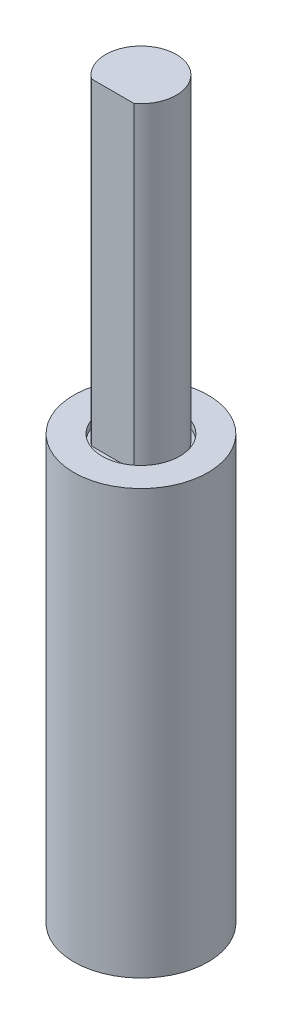
SolidWorks part; units mm, degrees
ref_plane "前视基准面" through (0, 0, 0) normal (0, 0, 1) x (1, 0, 0)
ref_plane "上视基准面" through (0, 0, 0) normal (0, 1, 0) x (1, 0, 0)
ref_plane "右视基准面" through (0, 0, 0) normal (1, 0, 0) x (0, 0, -1)
other "Configuration Table"
sketch "草图1" plane through (0, 0, 0) normal (0, 1, 0) x (1, 0, 0)
  circle A0 centre (0, 0) radius 4.75
  dimension "D1" = 9.5
extrude "凸台-拉伸1" add sketch "草图1" along normal blind 30
sketch "草图2" plane through (0, 30, 0) normal (0, 1, 0) x (1, 0, 0)
  circle A0 centre (0, 0) radius 2.75
  dimension "D1" = 5.5
extrude "切除-拉伸1" cut sketch "草图2" against normal blind 0.5
sketch "草图3" plane through (0, 29.5, 0) normal (0, 1, 0) x (1, 0, 0)
  circle A0 centre (0, 0) radius 2.5
  dimension "D1" = 5
extrude "凸台-拉伸2" add sketch "草图3" along normal blind 22.5
sketch "草图4" plane through (0, 0, 0) normal (0, -1, 0) x (1, 0, 0)
  circle A0 centre (0, 0) radius 2.5
  dimension "D1" = 5
extrude "凸台-拉伸3" add sketch "草图4" along normal blind 0.5
sketch "草图5" plane through (0, 52, 0) normal (0, 1, 0) x (1, 0, 0)
  line L0 (-1.5, -2) -> (1.5, -2)
  circle A0 centre (0, 0) radius 2.5
  circle M2 centre (0, 0) radius 2.5
  dimension "D2" = 5
  dimension "D1" = 2
extrude "切除-拉伸2" cut sketch "草图5" against normal blind 22.5 contours L0 M2
